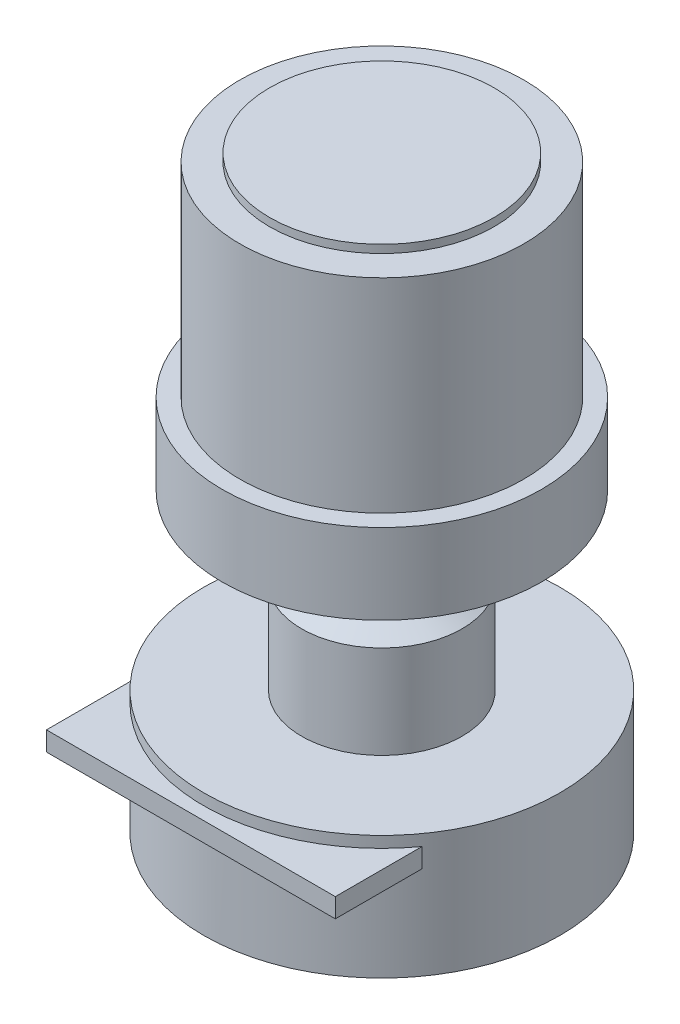
SolidWorks part; units mm, degrees
ref_plane "Plan de face" through (0, 0, 0) normal (0, 0, 1) x (1, 0, 0)
ref_plane "Plan de dessus" through (0, 0, 0) normal (0, 1, 0) x (1, 0, 0)
ref_plane "Plan de droite" through (0, 0, 0) normal (1, 0, 0) x (0, 0, -1)
ref_axis "Axe1" through (0, -55, 0) along (0, 1, 0)
sketch "Esquisse2" plane through (0, 0, 0) normal (0, 0, 1) x (1, 0, 0)
  line L0 (0, 17.7) -> (-8.85, 17.7)
  line L1 (0, -55) -> (0, 55) construction
  line L2 (-8.85, 17.7) -> (-8.85, 5)
  line L3 (-8.85, 5) -> (-9.95, 5)
  line L4 (-9.95, 5) -> (-9.95, 0)
  line L5 (-9.95, 0) -> (-3, 0)
  line L6 (-3, 0) -> (-3, -4)
  line L7 (-3, -4) -> (-5, -5)
  line L8 (-5, -5) -> (-5, -10.8)
  line L9 (-5, -10.8) -> (-11.1, -10.8)
  line L10 (-11.1, -10.8) -> (-11.1, -18.5)
  line L11 (-11.1, -18.5) -> (0, -18.5)
  line L12 (0, -18.5) -> (0, 17.7)
  point P14 (-4.3326, 12.751)
  point P15 (-5, 12.5988)
  point P16 (-11.1, 1.8038)
  point P17 (-5, 4.5378)
  point P18 (0, 0)
  dimension "D1" = 8.85
  dimension "D2" = 12.7
  dimension "D3" = 5
  dimension "D4" = 9.95
  dimension "D5" = 3
  dimension "D6" = 4
  dimension "D7" = 6.8
  dimension "D8" = 5
  dimension "D9" = 1
  dimension "D10" = 7.7
  dimension "D11" = 11.1
revolve "Révolution1" add sketch "Esquisse2" angle 360 about axis through (0, -55, 0) along (0, 1, 0)
sketch "Esquisse3" plane through (0, -18.5, 0) normal (0, -1, 0) x (1, 0, 0)
  line L0 (-9, 6.4969) -> (-9, 11.9)
  line L1 (-9, 11.9) -> (9, 11.9)
  line L2 (9, 11.9) -> (9, 6.4969)
  circle A0 centre (0, 0) radius 11.1 construction
  arc A1 (9, 6.4969) -> (-9, 6.4969) centre (0, 0) ccw
  point P6 (0, 11.9)
  point P7 (0, -11.1)
  point P9 (0, 0)
  dimension "D1" = 18
  dimension "D2" = 23
extrude "Boss.-Extru.1" add sketch "Esquisse3" along normal blind 1.2 from offset 7 contours L1 L2 A1 L0 offset against normal yes
sketch "Esquisse4" plane through (0, 17.7, 0) normal (0, 1, 0) x (1, 0, 0)
  circle A0 centre (0, 0) radius 7
  dimension "D1" = 14
extrude "Boss.-Extru.2" add sketch "Esquisse4" along normal blind 0.5
